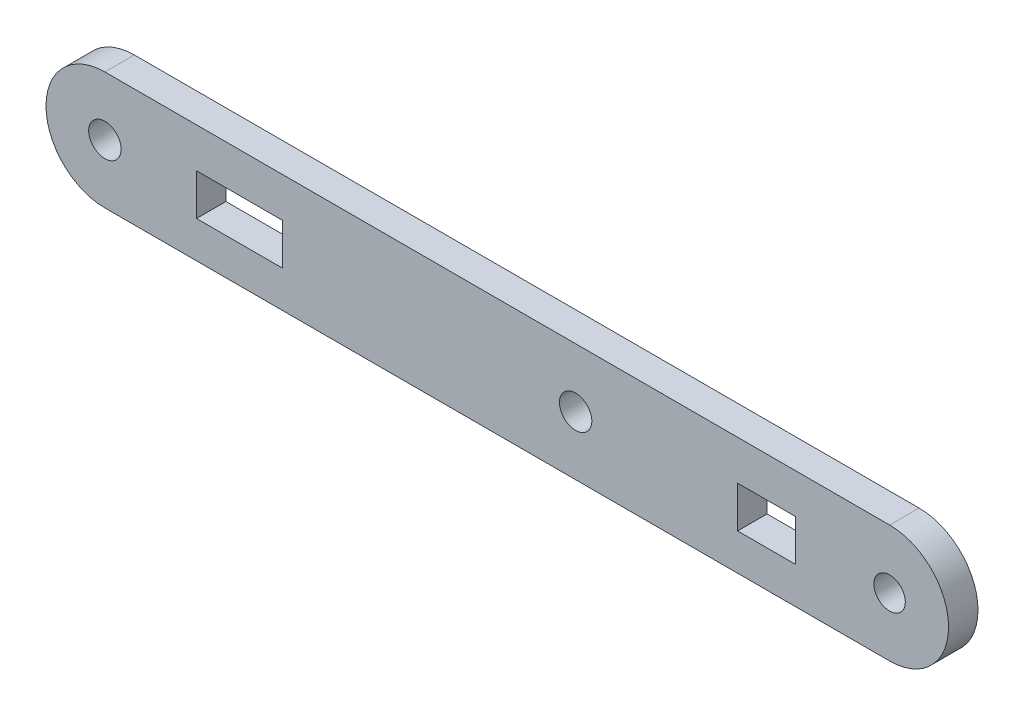
SolidWorks part; units mm, degrees
ref_plane "前视基准面" through (0, 0, 0) normal (0, 0, 1) x (1, 0, 0)
ref_plane "上视基准面" through (0, 0, 0) normal (0, 1, 0) x (1, 0, 0)
ref_plane "右视基准面" through (0, 0, 0) normal (1, 0, 0) x (0, 0, -1)
ref_plane "基准面4" through (0, 0, 0) normal (0, 0, -1) x (-1, 0, 0)
sketch "草图1" plane through (0, 0, 0) normal (0, 0, -1) x (-1, 0, 0)
  line L0 (40.0095, 3.7345) -> (31.2583, 3.7345)
  line L1 (31.2583, 3.7345) -> (31.2583, 7.9514)
  line L2 (31.2583, 7.9514) -> (40.0095, 7.9514)
  line L3 (40.0095, 7.9514) -> (40.0095, 3.7345)
  line L4 (-30.6182, 0) -> (49.3435, 0)
  line L5 (49.3435, 12) -> (-30.6182, 12)
  line L6 (-15.127, 7.9514) -> (-15.127, 3.7345)
  line L7 (-15.127, 3.7345) -> (-21.0271, 3.7345)
  line L8 (-21.0271, 3.7345) -> (-21.0271, 7.9514)
  line L9 (-21.0271, 7.9514) -> (-15.127, 7.9514)
  arc A0 (49.3435, 0) -> (49.3435, 12) centre (49.3435, 6) ccw
  arc A1 (-30.6182, 12) -> (-30.6182, 0) centre (-30.6182, 6) ccw
  circle A2 centre (49.3435, 6) radius 1.65
  circle A3 centre (1.3793, 6.0002) radius 1.3
  circle A4 centre (-30.6116, 6.0001) radius 1.6
extrude "凸台-拉伸1" add sketch "草图1" against normal blind 3
sketch "草图2" plane through (0, 0, 3) normal (0, 0, 1) x (1, 0, 0)
  circle A0 centre (-49.3435, 6) radius 1.65
  circle A1 centre (-1.3793, 6.0002) radius 1.65
  dimension "D1" = 3.3
extrude "切除-拉伸1" cut sketch "草图2" against normal through all
sketch "草图4" plane through (0, 0, 0) normal (0, 0, -1) x (-1, 0, 0)
  text T0 "2"
extrude "切除-拉伸3" cut sketch "草图4" against normal blind 1
